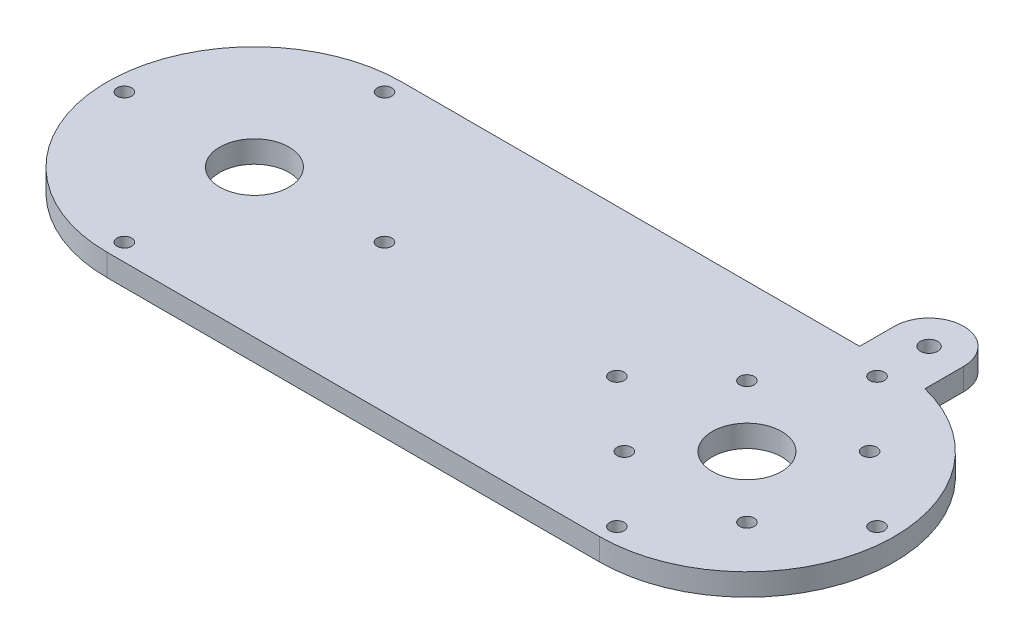
SolidWorks part; units mm, degrees
ref_plane "Front Plane" through (0, 0, 0) normal (0, 0, 1) x (1, 0, 0)
ref_plane "Top Plane" through (0, 0, 0) normal (0, 1, 0) x (1, 0, 0)
ref_plane "Right Plane" through (0, 0, 0) normal (1, 0, 0) x (0, 0, -1)
sketch "Sketch1" plane through (0, 0, 0) normal (0, 1, 0) x (1, 0, 0)
  line L0 (-142, 0) -> (0, 0) construction
  line L1 (-142, 42.5) -> (0, 42.5)
  line L6 (-142, -42.5) -> (0, -42.5)
  line L19 (17.6777, -17.6777) -> (-17.6777, 17.6777) construction
  line L21 (-17.6777, -17.6777) -> (17.6777, 17.6777) construction
  line L25 (-10, 41.3068) -> (-10, 52.5)
  line L26 (0, 0) -> (0, 29.185) construction
  line L27 (0, 29.185) -> (0, 52.5) construction
  line L28 (10, 52.5) -> (10, 41.3068)
  circle A1 centre (-142, 0) radius 10
  circle A4 centre (-142, 0) radius 14.2875 construction
  circle A5 centre (0, 0) radius 10
  circle A8 centre (-142, 0) radius 37.5 construction
  circle A13 centre (-142, 0) radius 42.5
  circle A14 centre (0, 0) radius 42.5
  circle A15 centre (0, 0) radius 37.5 construction
  circle A16 centre (0, 37.5) radius 2.1
  circle A17 centre (37.5, 0) radius 2.1
  circle A18 centre (0, -37.5) radius 2.1
  circle A19 centre (-37.5, 0) radius 2.1
  circle A28 centre (-142, 0) radius 27.94 construction
  circle A29 centre (0, 0) radius 25 construction
  circle A30 centre (-17.6777, 17.6777) radius 2.1
  circle A31 centre (17.6777, -17.6777) radius 2.1
  circle A32 centre (-17.6777, -17.6777) radius 2.1
  circle A33 centre (17.6777, 17.6777) radius 2.1
  circle A36 centre (0, 52.5) radius 2.5
  circle A37 centre (0, 52.5) radius 10
  circle A38 centre (-179.5, 0) radius 2.1
  circle A39 centre (-142, 37.5) radius 2.1
  circle A40 centre (-142, -37.5) radius 2.1
  circle A41 centre (-104.5, 0) radius 2.1
  dimension "D2" = 20
  dimension "D4" = 4.2
  dimension "D5" = 45
  dimension "D6" = 28.575
  dimension "D7" = 20
  dimension "D9" = 55.88
  dimension "D10" = 85
  dimension "D8" = 75
  dimension "D11" = 4.2
  dimension "D12" = 75
  dimension "D14" = 50
  dimension "D15" = 4.2
  dimension "D18" = 5
  dimension "D19" = 20
  dimension "D3" = 142
extrude "Boss-Extrude1" add sketch "Sketch1" against normal blind 6.35
